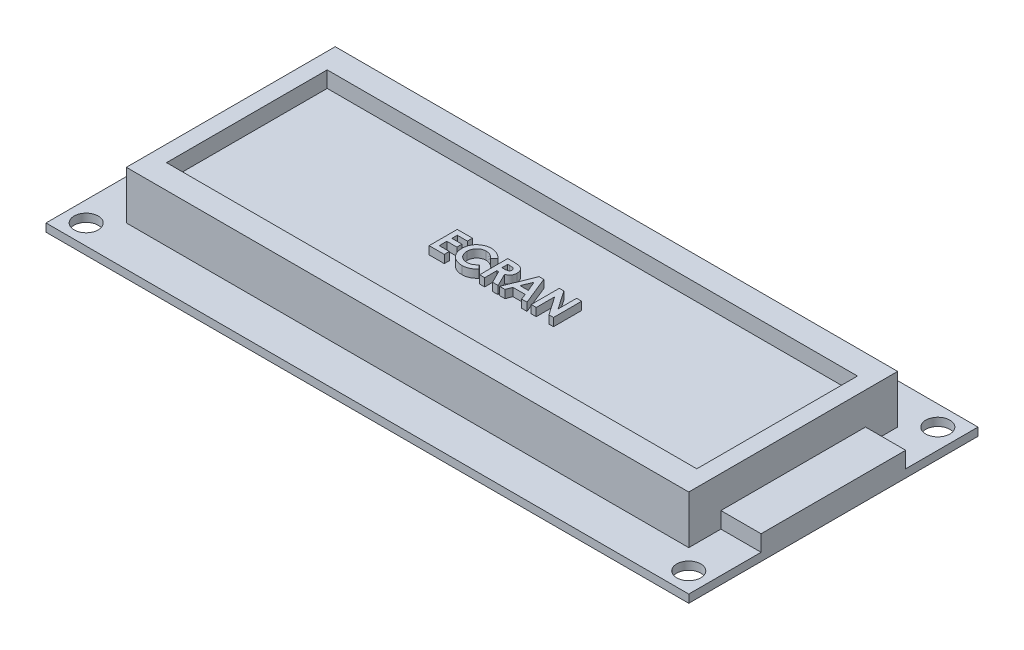
SolidWorks part; units mm, degrees
ref_plane "Plan de face" through (0, 0, 0) normal (0, 0, 1) x (1, 0, 0)
ref_plane "Plan de dessus" through (0, 0, 0) normal (0, 1, 0) x (1, 0, 0)
ref_plane "Plan de droite" through (0, 0, 0) normal (1, 0, 0) x (0, 0, -1)
sketch "Esquisse1" plane through (0, 0, 0) normal (0, 1, 0) x (1, 0, 0)
  line L1 (0, 0) -> (80, 0)
  line L2 (0, 0) -> (0, 36)
  line L3 (0, 36) -> (80, 36)
  line L4 (80, 0) -> (80, 36)
  circle A0 centre (2.5, 33.5) radius 1.5
  circle A1 centre (77.5, 33.5) radius 1.5
  circle A2 centre (2.5, 2.5) radius 1.5
  circle A3 centre (77.5, 2.5) radius 1.5
  dimension "D11" = 3
  dimension "D12" = 3
  dimension "D13" = 3
  dimension "D14" = 3
  dimension "D15" = 75
  dimension "D1" = 36
  dimension "D2" = 80
  dimension "D3" = 2.5
  dimension "D4" = 2.5
  dimension "D5" = 2.5
  dimension "D6" = 2.5
  dimension "D7" = 2.5
  dimension "D8" = 2.5
  dimension "D9" = 2.5
  dimension "D10" = 2.5
  dimension "D16" = 31
extrude "Plaque PCB" add sketch "Esquisse1" along normal blind 1
sketch "Esquisse2" plane through (0, 1, 0) normal (0, 1, 0) x (1, 0, 0)
  line L0 (80, 36) -> (0, 36) construction
  line L1 (5, 31) -> (75, 31)
  line L2 (5, 31) -> (5, 5)
  line L3 (5, 5) -> (75, 5)
  line L4 (75, 31) -> (75, 5)
  line L5 (0, 0) -> (80, 0) construction
  line L6 (80, 0) -> (80, 36) construction
  line L7 (0, 36) -> (0, 0) construction
  dimension "D1" = 5
  dimension "D2" = 5
  dimension "D3" = 5
  dimension "D4" = 5
extrude "Cadre ecran" add sketch "Esquisse2" along normal blind 6 contours L2 L1 L4 L3
sketch "Esquisse5" plane through (0, 7, 0) normal (0, 1, 0) x (1, 0, 0)
  line L0 (5, 31) -> (5, 5) construction
  line L1 (7, 28) -> (73, 28)
  line L2 (7, 28) -> (7, 8)
  line L3 (7, 8) -> (73, 8)
  line L4 (73, 28) -> (73, 8)
  line L5 (5, 31) -> (75, 31) construction
  line L6 (75, 31) -> (75, 5) construction
  line L7 (5, 5) -> (75, 5) construction
  dimension "D1" = 2
  dimension "D2" = 3
  dimension "D3" = 2
  dimension "D4" = 3
extrude "Vitre ecran" cut sketch "Esquisse5" against normal blind 2
sketch "Esquisse6" plane through (0, 5, 0) normal (0, 1, 0) x (1, 0, 0)
  text T0 "<b>ECRAN</b>"
extrude "Texte ECRAN" add sketch "Esquisse6" along normal blind 1
sketch "Esquisse9" plane through (0, 1, 0) normal (0, 1, 0) x (1, 0, 0)
  line L0 (80, 36) -> (80, 0) construction
  line L1 (80, 18) -> (75, 18) construction
  line L2 (75, 31) -> (75, 5) construction
  line L3 (80, 18) -> (80, 9)
  line L4 (80, 9) -> (75, 9)
  line L5 (75, 9) -> (75, 27)
  line L6 (75, 31) -> (75, 5) construction
  line L7 (75, 27) -> (80, 27)
  line L8 (80, 27) -> (80, 18)
  dimension "D1" = 9
  dimension "D2" = 9
extrude "Bloc Retroeclaireage" add sketch "Esquisse9" along normal blind 2
